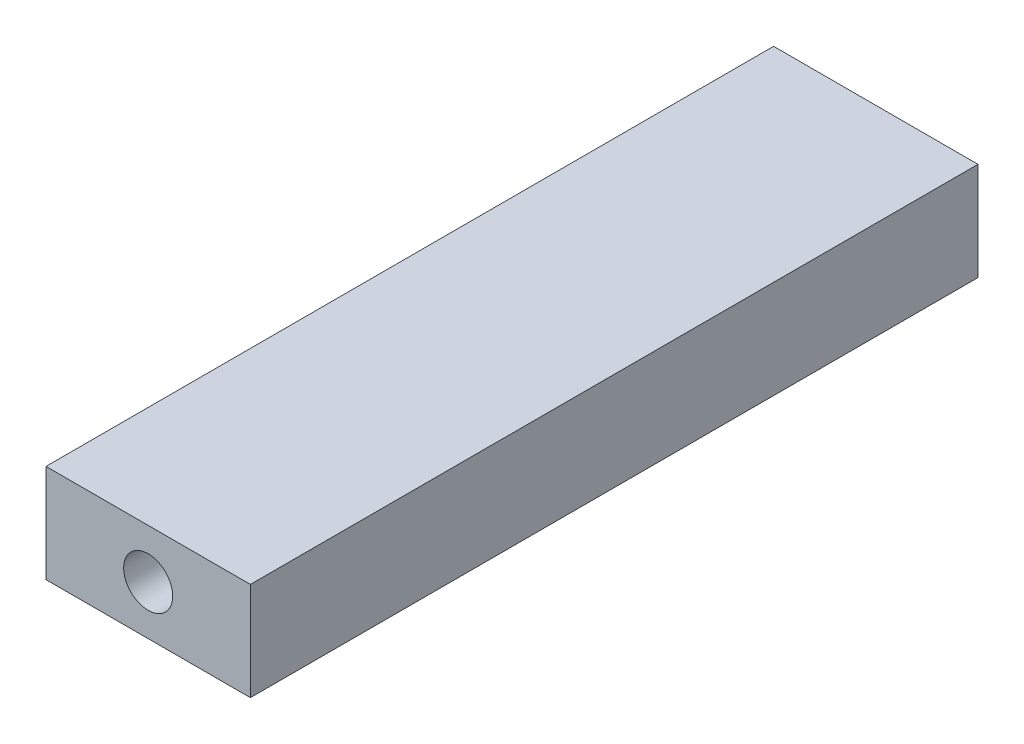
SolidWorks part; units mm, degrees
ref_plane "前视基准面" through (0, 0, 0) normal (0, 0, 1) x (1, 0, 0)
ref_plane "上视基准面" through (0, 0, 0) normal (0, 1, 0) x (1, 0, 0)
ref_plane "右视基准面" through (0, 0, 0) normal (1, 0, 0) x (0, 0, -1)
sketch "草图1" plane through (0, 0, 0) normal (0, 0, 1) x (1, 0, 0)
  line L1 (0, 0) -> (10, 0)
  line L2 (0, 0) -> (0, -4.8)
  line L3 (0, -4.8) -> (10, -4.8)
  line L4 (10, 0) -> (10, -4.8)
  dimension "D1" = 10
  dimension "D2" = 4.8
extrude "凸台-拉伸1" add sketch "草图1" along normal blind 35.6
sketch "草图2" plane through (0, 0, 35.6) normal (0, 0, 1) x (1, 0, 0)
  line L4 (0, 0) -> (0, -4.8)
  line L5 (0, -4.8) -> (10, -4.8)
  line L6 (10, -4.8) -> (10, 0)
  line L7 (10, 0) -> (0, 0)
  line L8 (0, 0) -> (0, -4.8)
  line L9 (0, -4.8) -> (10, -4.8)
  line L10 (10, -4.8) -> (10, 0)
  line L11 (10, 0) -> (0, 0)
  circle A0 centre (5, -2.4) radius 1.2
  point P7 (5, 0)
  point P9 (10, -2.4)
  dimension "D2" = 2.4
  dimension "D1" = 0
extrude "切除-拉伸1" cut sketch "草图2" against normal through all contours A0
